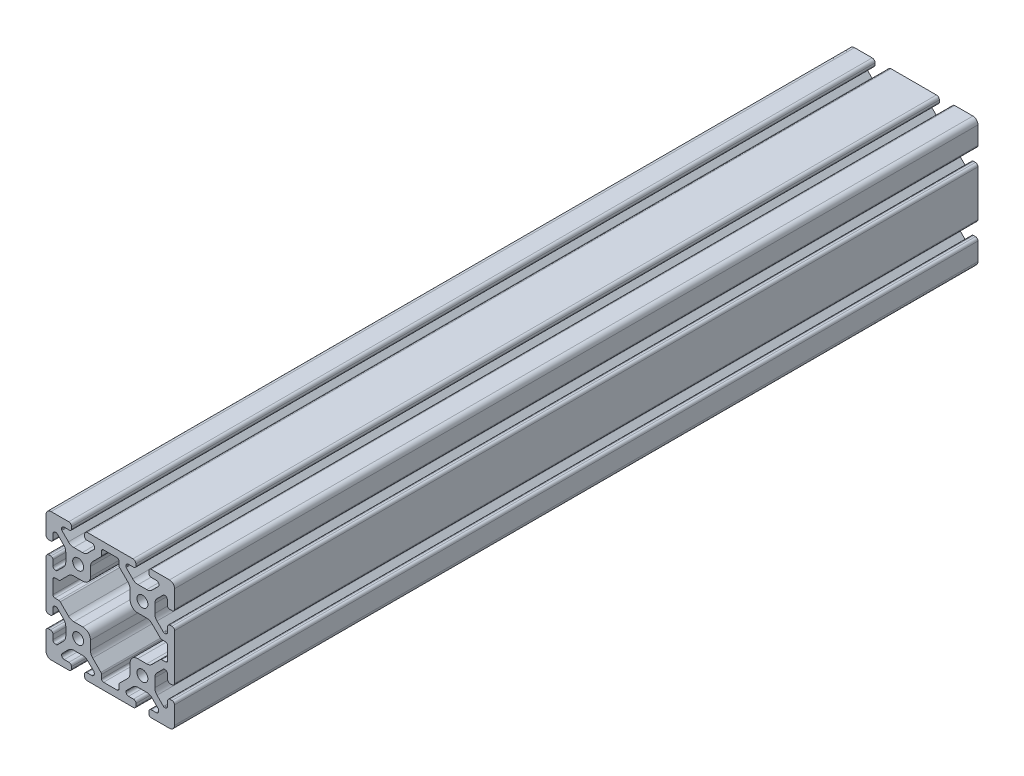
SolidWorks part; units mm, degrees
material "6061 Alloy"
ref_plane "Front Plane" through (0, 0, 0) normal (0, 0, 1) x (1, 0, 0)
ref_plane "Top Plane" through (0, 0, 0) normal (0, 1, 0) x (1, 0, 0)
ref_plane "Right Plane" through (0, 0, 0) normal (1, 0, 0) x (0, 0, -1)
sketch "Sketch1" plane through (0, 0, 0) normal (0, 0, 1) x (1, 0, 0)
  line L0 (0, -40) -> (0, 40) construction
  line L1 (0, 0) -> (-43.5804, 43.5804) construction
  line L2 (-20, 20) -> (-47.7323, 20) construction
  line L3 (-20, 20) -> (3.796, 43.796) construction
  line L4 (-20, 20) -> (-20, 43.5758) construction
  line L5 (-20, -27.7) -> (-20, -47.5576) construction
  line L7 (-36.8718, 24) -> (-28.8718, 24) construction
  line L8 (-36.8718, 24) -> (-36.8718, 16) construction
  line L9 (-36.8718, 16) -> (-28.8718, 16) construction
  line L10 (-28.8718, 24) -> (-28.8718, 16) construction
  line L11 (-36.8718, 24) -> (-28.8718, 16) construction
  line L12 (-36.8718, 16) -> (-28.8718, 24) construction
  line L131 (29.0912, 26.0365) -> (33.0827, 30.028)
  line L132 (27.7, 17.3222) -> (27.7, 22.6778)
  line L133 (29.0912, 13.9635) -> (33.0827, 9.972)
  line L134 (33.6201, 9.7494) -> (34.11, 9.7494)
  line L135 (35.68, 11.3194) -> (35.68, 14.2221)
  line L136 (37.25, 15.7921) -> (38.43, 15.7921)
  line L137 (40, 14.2221) -> (40, 7.0214)
  line L138 (40, 7.0214) -> (40, -7.0214)
  line L139 (40, -7.0214) -> (40, -14.2221)
  line L140 (38.43, -15.7921) -> (37.25, -15.7921)
  line L141 (35.68, -14.2221) -> (35.68, -11.3194)
  line L142 (33.6201, -9.7494) -> (34.11, -9.7494)
  line L143 (29.0912, -13.9635) -> (33.0827, -9.972)
  line L144 (27.7, -22.6778) -> (27.7, -17.3222)
  line L145 (29.0912, -26.0365) -> (33.0827, -30.028)
  line L146 (33.6201, -30.2506) -> (34.11, -30.2506)
  line L147 (35.68, -28.6806) -> (35.68, -25.7779)
  line L148 (37.25, -24.2079) -> (38.43, -24.2079)
  line L149 (40, -25.7779) -> (40, -33.0259)
  line L150 (40, -33.0259) -> (40, -36.83)
  line L151 (36.83, -40) -> (32.9998, -40)
  line L152 (32.9998, -40) -> (25.5696, -40)
  line L153 (23.9996, -38.43) -> (23.9996, -37.25)
  line L154 (25.5696, -35.68) -> (28.4723, -35.68)
  line L155 (30.0413, -34.0552) -> (30.0171, -33.3605)
  line L156 (29.7949, -32.8496) -> (26.0365, -29.0912)
  line L157 (17.3222, -27.7) -> (22.6778, -27.7)
  line L158 (10.035, -33.0197) -> (13.9635, -29.0912)
  line L159 (9.8124, -33.8926) -> (9.8124, -33.5571)
  line L160 (11.3824, -35.4626) -> (14.4246, -35.4626)
  line L161 (15.9946, -37.0326) -> (15.9946, -38.43)
  line L162 (14.4246, -40) -> (6.9987, -40)
  line L163 (6.9987, -40) -> (-6.9987, -40)
  line L164 (-6.9987, -40) -> (-14.4292, -40)
  line L165 (-15.9992, -38.43) -> (-15.9992, -37.25)
  line L166 (-14.4292, -35.68) -> (-11.5265, -35.68)
  line L167 (-9.9574, -34.0552) -> (-9.9816, -33.3618)
  line L168 (-10.2038, -32.8509) -> (-13.9635, -29.0912)
  line L169 (-22.6778, -27.7) -> (-17.3222, -27.7)
  line L170 (-30.028, -33.0827) -> (-26.0365, -29.0912)
  line L171 (-30.2506, -34.11) -> (-30.2506, -33.6201)
  line L172 (-28.6806, -35.68) -> (-25.7231, -35.68)
  line L173 (-24.1531, -37.25) -> (-24.1531, -38.43)
  line L174 (-25.7231, -40) -> (-33, -40)
  line L175 (-33, -40) -> (-36.83, -40)
  line L176 (-40, -36.83) -> (-40, -33.0191)
  line L177 (-40, -33.0191) -> (-40, -25.591)
  line L178 (-38.43, -24.021) -> (-37.25, -24.021)
  line L179 (-35.68, -28.4937) -> (-35.68, -25.591)
  line L180 (-34.0552, -30.0627) -> (-33.3827, -30.0392)
  line L181 (-32.8718, -29.8171) -> (-29.0912, -26.0365)
  line L182 (-27.7, -22.6778) -> (-27.7, -17.3222)
  line L183 (-29.0912, -13.9635) -> (-33.0827, -9.972)
  line L184 (-34.11, -9.7494) -> (-33.6201, -9.7494)
  line L185 (-35.68, -11.3194) -> (-35.68, -14.4473)
  line L186 (-38.43, -16.0173) -> (-37.25, -16.0173)
  line L187 (-40, -14.4473) -> (-40, -7.0169)
  line L188 (-40, -7.0169) -> (-40, 7.0169)
  line L189 (-40, 7.0169) -> (-40, 14.1348)
  line L190 (-38.1948, 15.94) -> (-36.9772, 15.94)
  line L191 (-35.68, 11.3194) -> (-35.68, 14.6428)
  line L192 (-34.11, 9.7494) -> (-33.6201, 9.7494)
  line L193 (-33.0827, 9.972) -> (-29.0912, 13.9635)
  line L194 (-27.7, 17.3222) -> (-27.7, 22.6778)
  line L195 (-29.0912, 26.0365) -> (-33.0827, 30.028)
  line L196 (-34.11, 30.2506) -> (-33.6201, 30.2506)
  line L197 (-35.68, 28.6806) -> (-35.68, 25.3572)
  line L198 (-38.1948, 24.06) -> (-36.9772, 24.06)
  line L199 (-40, 25.8652) -> (-40, 33.3181)
  line L200 (-40, 33.3181) -> (-40, 36.83)
  line L201 (-36.83, 40) -> (-33.0314, 40)
  line L202 (-33.0314, 40) -> (-25.8652, 40)
  line L203 (-24.06, 36.9772) -> (-24.06, 38.1948)
  line L204 (-25.3572, 35.68) -> (-28.7018, 35.68)
  line L205 (-30.285, 33.6069) -> (-30.285, 34.0968)
  line L206 (-30.0961, 33.1508) -> (-26.0365, 29.0912)
  line L207 (-22.6778, 27.7) -> (-17.3222, 27.7)
  line L208 (-13.9635, 29.0912) -> (-9.9039, 33.1508)
  line L209 (-9.715, 33.6069) -> (-9.715, 34.0968)
  line L210 (-14.6428, 35.68) -> (-11.2982, 35.68)
  line L211 (-15.94, 36.9772) -> (-15.94, 38.1948)
  line L212 (-14.1348, 40) -> (-6.9844, 40)
  line L213 (-6.9844, 40) -> (6.9844, 40)
  line L214 (6.9844, 40) -> (14.1348, 40)
  line L215 (15.94, 36.9772) -> (15.94, 38.1948)
  line L216 (14.6428, 35.68) -> (11.2982, 35.68)
  line L217 (9.715, 33.6069) -> (9.715, 34.0968)
  line L218 (9.9039, 33.1508) -> (13.9635, 29.0912)
  line L219 (17.3222, 27.7) -> (22.6778, 27.7)
  line L220 (26.0365, 29.0912) -> (30.028, 33.0827)
  line L221 (30.2506, 33.6201) -> (30.2506, 34.11)
  line L222 (25.5409, 35.679) -> (28.6258, 35.679)
  line L223 (23.9709, 37.249) -> (23.9709, 38.43)
  line L224 (25.5409, 40) -> (36.83, 40)
  line L226 (40, 36.83) -> (40, 32.9339)
  line L227 (40, 32.9339) -> (40, 25.7779)
  line L228 (38.43, 24.2079) -> (37.0956, 24.2079)
  line L229 (35.5256, 25.7779) -> (35.5256, 28.6806)
  line L230 (33.6201, 30.2506) -> (33.9556, 30.2506)
  line L231 (17.07, 12.32) -> (22.6578, 12.32)
  line L232 (26.0165, 10.9288) -> (31.1439, 5.8014)
  line L233 (32.0419, 5.4294) -> (34.41, 5.4294)
  line L234 (35.68, -4.1594) -> (35.68, 4.1594)
  line L235 (32.0419, -5.4294) -> (34.41, -5.4294)
  line L236 (26.0165, -10.9288) -> (31.1439, -5.8014)
  line L237 (17.07, -12.32) -> (22.6578, -12.32)
  line L238 (12.32, -22.6578) -> (12.32, -17.07)
  line L239 (5.8014, -31.1439) -> (10.9288, -26.0165)
  line L240 (5.4294, -34.41) -> (5.4294, -32.0419)
  line L241 (-4.1594, -35.68) -> (4.1594, -35.68)
  line L242 (-5.4294, -34.41) -> (-5.4294, -32.0419)
  line L243 (-5.8014, -31.1439) -> (-10.9288, -26.0165)
  line L244 (-12.32, -22.6578) -> (-12.32, -17.07)
  line L245 (-22.6578, -12.32) -> (-17.07, -12.32)
  line L246 (-26.0165, -10.9288) -> (-31.1439, -5.8014)
  line L247 (-34.41, -5.4294) -> (-32.0419, -5.4294)
  line L248 (-35.68, -4.1594) -> (-35.68, 4.1594)
  line L249 (-34.41, 5.4294) -> (-32.0419, 5.4294)
  line L250 (-31.1439, 5.8014) -> (-26.0165, 10.9288)
  line L251 (-22.6578, 12.32) -> (-17.07, 12.32)
  line L252 (-12.32, 17.07) -> (-12.32, 22.6578)
  line L253 (-10.9288, 26.0165) -> (-5.8014, 31.1439)
  line L254 (-5.4294, 32.0419) -> (-5.4294, 34.41)
  line L255 (-4.1594, 35.68) -> (4.1594, 35.68)
  line L256 (5.4294, 32.0419) -> (5.4294, 34.41)
  line L257 (5.8014, 31.1439) -> (10.9288, 26.0165)
  line L258 (12.32, 17.07) -> (12.32, 22.6578)
  line L260 (-40, 0) -> (40, 0) construction
  circle A0 centre (-32.8718, 20) radius 4 construction
  circle A116 centre (-20, 20) radius 3.4
  circle A117 centre (20, 20) radius 3.4
  circle A118 centre (20, -20) radius 3.4
  circle A119 centre (-20, -20) radius 3.4
  arc A120 (29.0912, 26.0365) -> (27.7, 22.6778) centre (32.45, 22.6778) ccw
  arc A121 (27.7, 17.3222) -> (29.0912, 13.9635) centre (32.45, 17.3222) ccw
  arc A122 (33.0827, 9.972) -> (33.6201, 9.7494) centre (33.6201, 10.5094) ccw
  arc A123 (34.11, 9.7494) -> (35.68, 11.3194) centre (34.11, 11.3194) ccw
  arc A124 (37.25, 15.7921) -> (35.68, 14.2221) centre (37.25, 14.2221) ccw
  arc A125 (40, 14.2221) -> (38.43, 15.7921) centre (38.43, 14.2221) ccw
  arc A126 (38.43, -15.7921) -> (40, -14.2221) centre (38.43, -14.2221) ccw
  arc A127 (35.68, -14.2221) -> (37.25, -15.7921) centre (37.25, -14.2221) ccw
  arc A128 (35.68, -11.3194) -> (34.11, -9.7494) centre (34.11, -11.3194) ccw
  arc A129 (33.6201, -9.7494) -> (33.0827, -9.972) centre (33.6201, -10.5094) ccw
  arc A130 (29.0912, -13.9635) -> (27.7, -17.3222) centre (32.45, -17.3222) ccw
  arc A131 (27.7, -22.6778) -> (29.0912, -26.0365) centre (32.45, -22.6778) ccw
  arc A132 (33.0827, -30.028) -> (33.6201, -30.2506) centre (33.6201, -29.4906) ccw
  arc A133 (34.11, -30.2506) -> (35.68, -28.6806) centre (34.11, -28.6806) ccw
  arc A134 (37.25, -24.2079) -> (35.68, -25.7779) centre (37.25, -25.7779) ccw
  arc A135 (40, -25.7779) -> (38.43, -24.2079) centre (38.43, -25.7779) ccw
  arc A136 (36.83, -40) -> (40, -36.83) centre (36.83, -36.83) ccw
  arc A137 (23.9996, -38.43) -> (25.5696, -40) centre (25.5696, -38.43) ccw
  arc A138 (25.5696, -35.68) -> (23.9996, -37.25) centre (25.5696, -37.25) ccw
  arc A139 (28.4723, -35.68) -> (30.0413, -34.0552) centre (28.4723, -34.11) ccw
  arc A140 (30.0171, -33.3605) -> (29.7949, -32.8496) centre (29.2575, -33.387) ccw
  arc A141 (26.0365, -29.0912) -> (22.6778, -27.7) centre (22.6778, -32.45) ccw
  arc A142 (17.3222, -27.7) -> (13.9635, -29.0912) centre (17.3222, -32.45) ccw
  arc A143 (10.035, -33.0197) -> (9.8124, -33.5571) centre (10.5724, -33.5571) ccw
  arc A144 (9.8124, -33.8926) -> (11.3824, -35.4626) centre (11.3824, -33.8926) ccw
  arc A145 (15.9946, -37.0326) -> (14.4246, -35.4626) centre (14.4246, -37.0326) ccw
  arc A146 (14.4246, -40) -> (15.9946, -38.43) centre (14.4246, -38.43) ccw
  arc A147 (-15.9992, -38.43) -> (-14.4292, -40) centre (-14.4292, -38.43) ccw
  arc A148 (-14.4292, -35.68) -> (-15.9992, -37.25) centre (-14.4292, -37.25) ccw
  arc A149 (-11.5265, -35.68) -> (-9.9574, -34.0552) centre (-11.5265, -34.11) ccw
  arc A150 (-9.9816, -33.3618) -> (-10.2038, -32.8509) centre (-10.7412, -33.3883) ccw
  arc A151 (-13.9635, -29.0912) -> (-17.3222, -27.7) centre (-17.3222, -32.45) ccw
  arc A152 (-22.6778, -27.7) -> (-26.0365, -29.0912) centre (-22.6778, -32.45) ccw
  arc A153 (-30.028, -33.0827) -> (-30.2506, -33.6201) centre (-29.4906, -33.6201) ccw
  arc A154 (-30.2506, -34.11) -> (-28.6806, -35.68) centre (-28.6806, -34.11) ccw
  arc A155 (-24.1531, -37.25) -> (-25.7231, -35.68) centre (-25.7231, -37.25) ccw
  arc A156 (-25.7231, -40) -> (-24.1531, -38.43) centre (-25.7231, -38.43) ccw
  arc A157 (-40, -36.83) -> (-36.83, -40) centre (-36.83, -36.83) ccw
  arc A158 (-38.43, -24.021) -> (-40, -25.591) centre (-38.43, -25.591) ccw
  arc A159 (-35.68, -25.591) -> (-37.25, -24.021) centre (-37.25, -25.591) ccw
  arc A160 (-35.68, -28.4937) -> (-34.0552, -30.0627) centre (-34.11, -28.4937) ccw
  arc A161 (-33.3827, -30.0392) -> (-32.8718, -29.8171) centre (-33.4092, -29.2797) ccw
  arc A162 (-29.0912, -26.0365) -> (-27.7, -22.6778) centre (-32.45, -22.6778) ccw
  arc A163 (-27.7, -17.3222) -> (-29.0912, -13.9635) centre (-32.45, -17.3222) ccw
  arc A164 (-33.0827, -9.972) -> (-33.6201, -9.7494) centre (-33.6201, -10.5094) ccw
  arc A165 (-34.11, -9.7494) -> (-35.68, -11.3194) centre (-34.11, -11.3194) ccw
  arc A166 (-37.25, -16.0173) -> (-35.68, -14.4473) centre (-37.25, -14.4473) ccw
  arc A167 (-40, -14.4473) -> (-38.43, -16.0173) centre (-38.43, -14.4473) ccw
  arc A168 (-38.1948, 15.94) -> (-40, 14.1348) centre (-38.1948, 14.1348) ccw
  arc A169 (-35.68, 14.6428) -> (-36.9772, 15.94) centre (-36.9772, 14.6428) ccw
  arc A170 (-35.68, 11.3194) -> (-34.11, 9.7494) centre (-34.11, 11.3194) ccw
  arc A171 (-33.6201, 9.7494) -> (-33.0827, 9.972) centre (-33.6201, 10.5094) ccw
  arc A172 (-29.0912, 13.9635) -> (-27.7, 17.3222) centre (-32.45, 17.3222) ccw
  arc A173 (-27.7, 22.6778) -> (-29.0912, 26.0365) centre (-32.45, 22.6778) ccw
  arc A174 (-33.0827, 30.028) -> (-33.6201, 30.2506) centre (-33.6201, 29.4906) ccw
  arc A175 (-34.11, 30.2506) -> (-35.68, 28.6806) centre (-34.11, 28.6806) ccw
  arc A176 (-36.9772, 24.06) -> (-35.68, 25.3572) centre (-36.9772, 25.3572) ccw
  arc A177 (-40, 25.8652) -> (-38.1948, 24.06) centre (-38.1948, 25.8652) ccw
  arc A178 (-36.83, 40) -> (-40, 36.83) centre (-36.83, 36.83) ccw
  arc A179 (-24.06, 38.1948) -> (-25.8652, 40) centre (-25.8652, 38.1948) ccw
  arc A180 (-25.3572, 35.68) -> (-24.06, 36.9772) centre (-25.3572, 36.9772) ccw
  arc A181 (-28.7018, 35.68) -> (-30.285, 34.0968) centre (-28.7018, 34.0968) ccw
  arc A182 (-30.285, 33.6069) -> (-30.0961, 33.1508) centre (-29.6399, 33.6069) ccw
  arc A183 (-26.0365, 29.0912) -> (-22.6778, 27.7) centre (-22.6778, 32.45) ccw
  arc A184 (-17.3222, 27.7) -> (-13.9635, 29.0912) centre (-17.3222, 32.45) ccw
  arc A185 (-9.9039, 33.1508) -> (-9.715, 33.6069) centre (-10.3601, 33.6069) ccw
  arc A186 (-9.715, 34.0968) -> (-11.2982, 35.68) centre (-11.2982, 34.0968) ccw
  arc A187 (-15.94, 36.9772) -> (-14.6428, 35.68) centre (-14.6428, 36.9772) ccw
  arc A188 (-14.1348, 40) -> (-15.94, 38.1948) centre (-14.1348, 38.1948) ccw
  arc A189 (15.94, 38.1948) -> (14.1348, 40) centre (14.1348, 38.1948) ccw
  arc A190 (14.6428, 35.68) -> (15.94, 36.9772) centre (14.6428, 36.9772) ccw
  arc A191 (11.2982, 35.68) -> (9.715, 34.0968) centre (11.2982, 34.0968) ccw
  arc A192 (9.715, 33.6069) -> (9.9039, 33.1508) centre (10.3601, 33.6069) ccw
  arc A193 (13.9635, 29.0912) -> (17.3222, 27.7) centre (17.3222, 32.45) ccw
  arc A194 (22.6778, 27.7) -> (26.0365, 29.0912) centre (22.6778, 32.45) ccw
  arc A195 (30.028, 33.0827) -> (30.2506, 33.6201) centre (29.4906, 33.6201) ccw
  arc A196 (30.2506, 34.11) -> (28.6258, 35.679) centre (28.6806, 34.11) ccw
  arc A197 (23.9709, 37.249) -> (25.5409, 35.679) centre (25.5409, 37.249) ccw
  arc A198 (25.5409, 40) -> (23.9709, 38.43) centre (25.5409, 38.43) ccw
  arc A199 (40, 36.83) -> (36.83, 40) centre (36.83, 36.83) ccw
  arc A200 (38.43, 24.2079) -> (40, 25.7779) centre (38.43, 25.7779) ccw
  arc A201 (35.5256, 25.7779) -> (37.0956, 24.2079) centre (37.0956, 25.7779) ccw
  arc A202 (35.5256, 28.6806) -> (33.9556, 30.2506) centre (33.9556, 28.6806) ccw
  arc A203 (33.6201, 30.2506) -> (33.0827, 30.028) centre (33.6201, 29.4906) ccw
  arc A204 (26.0165, 10.9288) -> (22.6578, 12.32) centre (22.6578, 7.57) ccw
  arc A205 (31.1439, 5.8014) -> (32.0419, 5.4294) centre (32.0419, 6.6994) ccw
  arc A206 (35.68, 4.1594) -> (34.41, 5.4294) centre (34.41, 4.1594) ccw
  arc A207 (34.41, -5.4294) -> (35.68, -4.1594) centre (34.41, -4.1594) ccw
  arc A208 (32.0419, -5.4294) -> (31.1439, -5.8014) centre (32.0419, -6.6994) ccw
  arc A209 (22.6578, -12.32) -> (26.0165, -10.9288) centre (22.6578, -7.57) ccw
  arc A210 (17.07, -12.32) -> (12.32, -17.07) centre (17.07, -17.07) ccw
  arc A211 (10.9288, -26.0165) -> (12.32, -22.6578) centre (7.57, -22.6578) ccw
  arc A212 (5.8014, -31.1439) -> (5.4294, -32.0419) centre (6.6994, -32.0419) ccw
  arc A213 (4.1594, -35.68) -> (5.4294, -34.41) centre (4.1594, -34.41) ccw
  arc A214 (-5.4294, -34.41) -> (-4.1594, -35.68) centre (-4.1594, -34.41) ccw
  arc A215 (-5.4294, -32.0419) -> (-5.8014, -31.1439) centre (-6.6994, -32.0419) ccw
  arc A216 (-12.32, -22.6578) -> (-10.9288, -26.0165) centre (-7.57, -22.6578) ccw
  arc A217 (-12.32, -17.07) -> (-17.07, -12.32) centre (-17.07, -17.07) ccw
  arc A218 (-26.0165, -10.9288) -> (-22.6578, -12.32) centre (-22.6578, -7.57) ccw
  arc A219 (-31.1439, -5.8014) -> (-32.0419, -5.4294) centre (-32.0419, -6.6994) ccw
  arc A220 (-35.68, -4.1594) -> (-34.41, -5.4294) centre (-34.41, -4.1594) ccw
  arc A221 (-34.41, 5.4294) -> (-35.68, 4.1594) centre (-34.41, 4.1594) ccw
  arc A222 (-32.0419, 5.4294) -> (-31.1439, 5.8014) centre (-32.0419, 6.6994) ccw
  arc A223 (-22.6578, 12.32) -> (-26.0165, 10.9288) centre (-22.6578, 7.57) ccw
  arc A224 (-17.07, 12.32) -> (-12.32, 17.07) centre (-17.07, 17.07) ccw
  arc A225 (-10.9288, 26.0165) -> (-12.32, 22.6578) centre (-7.57, 22.6578) ccw
  arc A226 (-5.8014, 31.1439) -> (-5.4294, 32.0419) centre (-6.6994, 32.0419) ccw
  arc A227 (-4.1594, 35.68) -> (-5.4294, 34.41) centre (-4.1594, 34.41) ccw
  arc A228 (5.4294, 34.41) -> (4.1594, 35.68) centre (4.1594, 34.41) ccw
  arc A229 (5.4294, 32.0419) -> (5.8014, 31.1439) centre (6.6994, 32.0419) ccw
  arc A230 (12.32, 22.6578) -> (10.9288, 26.0165) centre (7.57, 22.6578) ccw
  arc A231 (12.32, 17.07) -> (17.07, 12.32) centre (17.07, 17.07) ccw
  point P9 (-32.8718, 20)
  dimension "D8" = 6.8
  dimension "D1" = 80
  dimension "D2" = 40
  dimension "D3" = 20
  dimension "D4" = 20.57
  dimension "D5" = 4.32
  dimension "D6" = 4.32
  dimension "D7" = 8.12
  dimension "D9" = 4.32
  dimension "D10" = 12.3
  dimension "D11" = 8
  dimension "D12" = 8
extrude "Extrude1" add sketch "Sketch1" against normal blind 500
